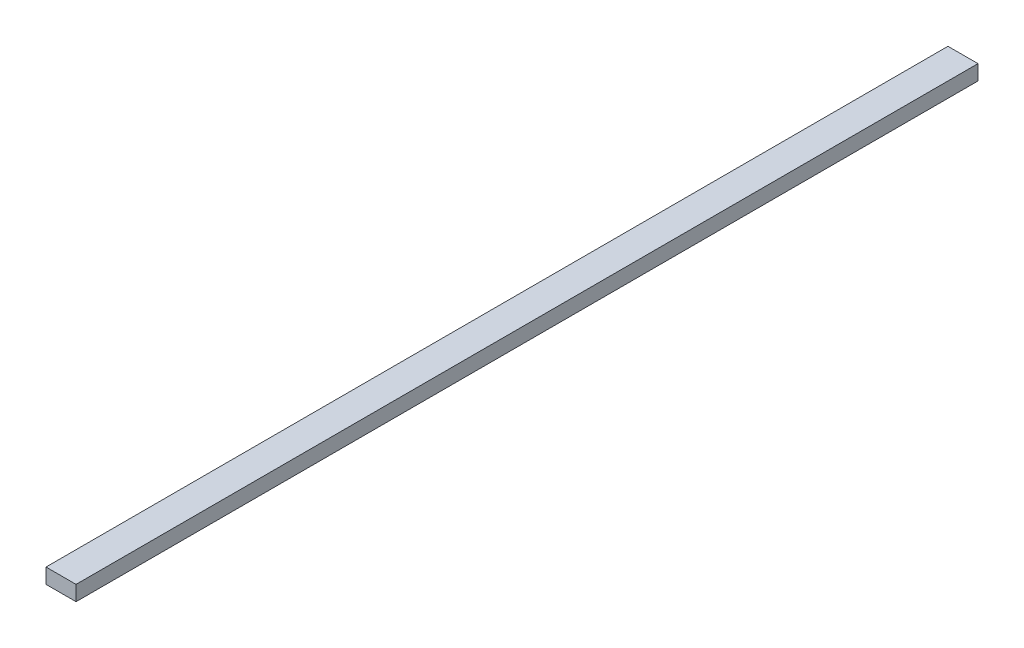
SolidWorks part; units mm, degrees
ref_plane "Front Plane" through (0, 0, 0) normal (0, 0, 1) x (1, 0, 0)
ref_plane "Top Plane" through (0, 0, 0) normal (0, 1, 0) x (1, 0, 0)
ref_plane "Right Plane" through (0, 0, 0) normal (1, 0, 0) x (0, 0, -1)
sketch "Sketch1" plane through (0, 0, 0) normal (0, 1, 0) x (1, 0, 0)
  line L1 (9.9918, 65.1031) -> (0, 65.1031)
  line L2 (9.9918, 65.1031) -> (9.9918, -234.8969)
  line L3 (9.9918, -234.8969) -> (0, -234.8969)
  line L4 (0, 65.1031) -> (0, -234.8969)
  dimension "D1" = 300
extrude "Boss-Extrude1" add sketch "Sketch1" along normal blind 5
